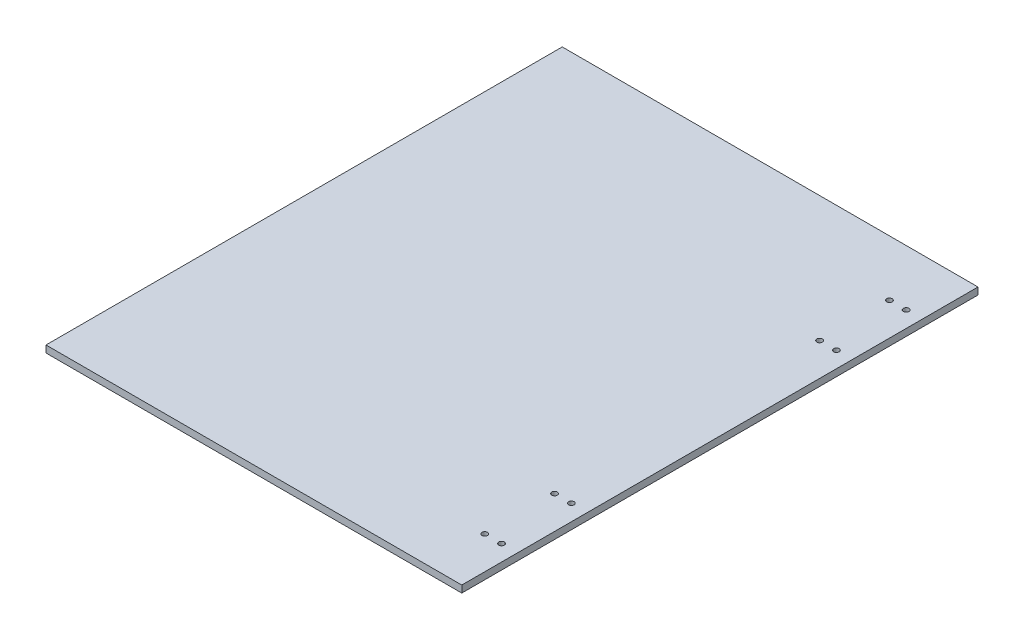
SolidWorks part; units mm, degrees
material "아크릴(내충격성)"
ref_plane "정면" through (0, 0, 0) normal (0, 0, 1) x (1, 0, 0)
ref_plane "윗면" through (0, 0, 0) normal (0, 1, 0) x (1, 0, 0)
ref_plane "우측면" through (0, 0, 0) normal (1, 0, 0) x (0, 0, -1)
sketch "스케치1" plane through (0, 0, 0) normal (0, 1, 0) x (1, 0, 0)
  line L0 (145.25, 185) -> (145.25, -185)
  line L1 (-152.75, 185) -> (145.25, 185)
  line L2 (-152.75, 185) -> (-152.75, -185)
  line L3 (-152.75, -185) -> (145.25, -185)
  line L5 (-152.75, 185) -> (152.75, -185) construction
  line L6 (-152.75, -185) -> (152.75, 185) construction
  point P0 (0, 0)
  dimension "D1" = 370
  dimension "D3" = 298
extrude "보스-돌출1" add sketch "스케치1" along normal blind 5
sketch "스케치2" plane through (0, 5, 0) normal (0, 1, 0) x (1, 0, 0)
  line L0 (133.75, 185) -> (133.75, -185) construction
  line L1 (145.25, 185) -> (-152.75, 185) construction
  line L2 (-152.75, -185) -> (145.25, -185) construction
  line L3 (121.75, 185) -> (121.75, -185) construction
  line L4 (145.25, -185) -> (145.25, 185) construction
  circle A0 centre (121.75, 145) radius 2
  circle A1 centre (133.75, 145) radius 2
  circle A2 centre (121.75, 95) radius 2
  circle A3 centre (133.75, 95) radius 2
  circle A4 centre (133.75, -95) radius 2
  circle A5 centre (121.75, -95) radius 2
  circle A6 centre (133.75, -145) radius 2
  circle A7 centre (121.75, -145) radius 2
  dimension "D1" = 11.5
  dimension "D6" = 12
extrude "컷-돌출1" cut sketch "스케치2" against normal through all
